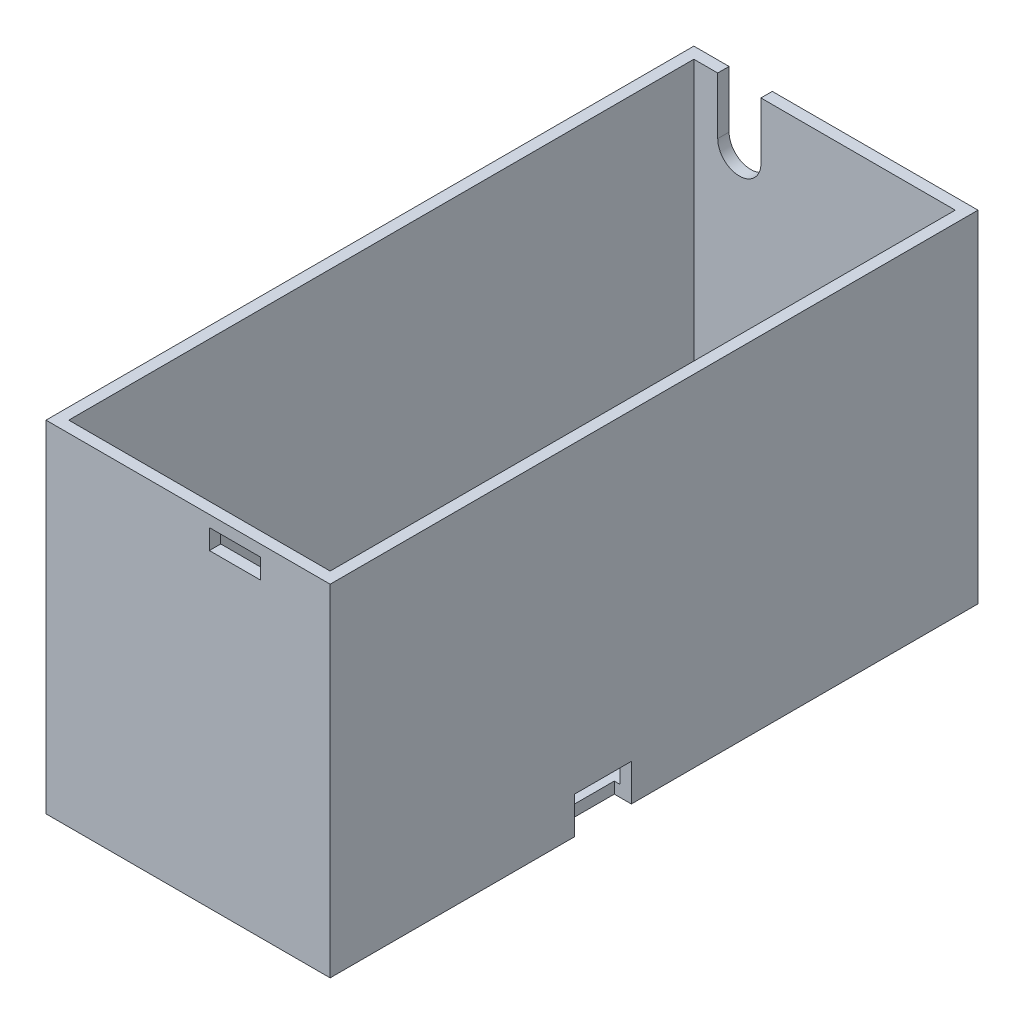
SolidWorks part; units mm, degrees
ref_plane "Ebene vorne" through (0, 0, 0) normal (0, 0, 1) x (1, 0, 0)
ref_plane "Ebene oben" through (0, 0, 0) normal (0, 1, 0) x (1, 0, 0)
ref_plane "Ebene rechts" through (0, 0, 0) normal (1, 0, 0) x (0, 0, -1)
sketch "Skizze1" plane through (0, 0, 0) normal (0, 1, 0) x (1, 0, 0)
  line L1 (-21.2423, 10.7747) -> (28.7577, 10.7747)
  line L2 (-21.2423, 10.7747) -> (-21.2423, -103.2253)
  line L3 (-21.2423, -103.2253) -> (28.7577, -103.2253)
  line L4 (28.7577, 10.7747) -> (28.7577, -103.2253)
  dimension "D1" = 50
  dimension "D2" = 114
extrude "Aufsatz-Linear austragen1" add sketch "Skizze1" along normal blind 60
sketch "Skizze2" plane through (0, 60, 0) normal (0, 1, 0) x (1, 0, 0)
  line L0 (-21.2423, 10.7747) -> (-21.2423, -103.2253) construction
  line L1 (28.7577, -103.2253) -> (28.7577, 10.7747) construction
  line L2 (-19.2423, 8.7747) -> (26.7577, 8.7747)
  line L3 (-19.2423, 8.7747) -> (-19.2423, -101.2253)
  line L4 (-19.2423, -101.2253) -> (26.7577, -101.2253)
  line L5 (26.7577, 8.7747) -> (26.7577, -101.2253)
  line L6 (28.7577, 10.7747) -> (-21.2423, 10.7747) construction
  line L7 (-21.2423, -103.2253) -> (28.7577, -103.2253) construction
  dimension "D1" = 2
  dimension "D2" = 2
  dimension "D3" = 2
  dimension "D4" = 2
extrude "Schnitt-Linear austragen1" cut sketch "Skizze2" against normal blind 58
sketch "Skizze3" plane through (0, 2, 0) normal (0, 1, 0) x (1, 0, 0)
  line L0 (3.7577, 8.7747) -> (3.7577, -101.2253) construction
  line L1 (26.7577, 8.7747) -> (-19.2423, 8.7747) construction
  line L2 (-19.2423, -101.2253) -> (26.7577, -101.2253) construction
  line L4 (-19.2423, 8.7747) -> (-19.2423, -101.2253) construction
  line L5 (-19.2423, -46.2253) -> (26.7577, -46.2253) construction
  line L6 (26.7577, -101.2253) -> (26.7577, 8.7747) construction
  circle A0 centre (-11.2423, -24.2253) radius 2
  circle A1 centre (18.7577, -24.2253) radius 2
  circle A2 centre (18.7577, -96.2253) radius 2
  circle A3 centre (-11.2423, -96.2253) radius 2
  dimension "D1" = 4
  dimension "D2" = 4
  dimension "D3" = 4
  dimension "D4" = 4
  dimension "D5" = 15
  dimension "D6" = 15
  dimension "D7" = 15
  dimension "D8" = 15
  dimension "D9" = 5
  dimension "D10" = 5
  dimension "D11" = 72
  dimension "D12" = 72
extrude "Aufsatz-Linear austragen2" add sketch "Skizze3" along normal blind 15.2
sketch "Skizze4" plane through (0, 17.2, 0) normal (0, 1, 0) x (1, 0, 0)
  circle A0 centre (-11.2423, -24.2253) radius 0.5
  circle A1 centre (18.7577, -24.2253) radius 0.5
  circle A2 centre (18.7577, -96.2253) radius 0.5
  circle A3 centre (-11.2423, -96.2253) radius 0.5
  dimension "D1" = 1
  dimension "D2" = 1
  dimension "D3" = 1
  dimension "D4" = 1
extrude "Schnitt-Linear austragen2" cut sketch "Skizze4" against normal blind 5
sketch "Skizze5" plane through (0, 2, 0) normal (0, 1, 0) x (1, 0, 0)
  line L0 (26.7577, 8.7747) -> (-19.2423, 8.7747) construction
  line L1 (-3.9923, -7.7253) -> (11.5077, -7.7253)
  line L2 (-3.9923, -7.7253) -> (-3.9923, -27.9253)
  line L3 (-3.9923, -27.9253) -> (11.5077, -27.9253)
  line L4 (11.5077, -7.7253) -> (11.5077, -27.9253)
  point P4 (3.7577, 8.7747)
  point P9 (3.7577, -7.7253)
  dimension "D1" = 15.5
  dimension "D2" = 20.2
  dimension "D3" = 16.5
extrude "Schnitt-Linear austragen3" cut sketch "Skizze5" against normal up to next
sketch "Skizze6" plane through (0, 2, 0) normal (0, 1, 0) x (1, 0, 0)
  line L0 (11.5077, -27.9253) -> (11.5077, -7.7253) construction
  line L1 (-3.9923, -27.9253) -> (11.5077, -27.9253)
  line L2 (-3.9923, -27.9253) -> (-3.9923, -29.9253)
  line L3 (-3.9923, -29.9253) -> (11.5077, -29.9253)
  line L4 (11.5077, -27.9253) -> (11.5077, -29.9253)
  dimension "D1" = 2
extrude "Aufsatz-Linear austragen3" add sketch "Skizze6" along normal blind 1
sketch "Skizze7" plane through (0, 2, 0) normal (0, 1, 0) x (1, 0, 0)
  line L0 (26.7577, 8.7747) -> (-19.2423, 8.7747) construction
  line L1 (-16.2423, -33.2253) -> (23.7577, -33.2253)
  line L2 (-16.2423, -33.2253) -> (-16.2423, -36.3253)
  line L3 (-16.2423, -36.3253) -> (23.7577, -36.3253)
  line L4 (23.7577, -33.2253) -> (23.7577, -36.3253)
  line L17 (-16.2423, -37.3253) -> (-16.2423, -40.4253)
  line L18 (-16.2423, -37.3253) -> (23.7577, -37.3253)
  line L19 (23.7577, -37.3253) -> (23.7577, -40.4253)
  line L20 (-16.2423, -40.4253) -> (23.7577, -40.4253)
  line L21 (-16.2423, -41.4253) -> (-16.2423, -44.5253)
  line L22 (-16.2423, -41.4253) -> (23.7577, -41.4253)
  line L23 (23.7577, -41.4253) -> (23.7577, -44.5253)
  line L24 (-16.2423, -44.5253) -> (23.7577, -44.5253)
  line L25 (-16.2423, -45.5253) -> (-16.2423, -48.6253)
  line L26 (-16.2423, -45.5253) -> (23.7577, -45.5253)
  line L27 (23.7577, -45.5253) -> (23.7577, -48.6253)
  line L28 (-16.2423, -48.6253) -> (23.7577, -48.6253)
  line L29 (-16.2423, -49.6253) -> (-16.2423, -52.7253)
  line L30 (-16.2423, -49.6253) -> (23.7577, -49.6253)
  line L31 (23.7577, -49.6253) -> (23.7577, -52.7253)
  line L32 (-16.2423, -52.7253) -> (23.7577, -52.7253)
  line L33 (-16.2423, -53.7253) -> (-16.2423, -56.8253)
  line L34 (-16.2423, -53.7253) -> (23.7577, -53.7253)
  line L35 (23.7577, -53.7253) -> (23.7577, -56.8253)
  line L36 (-16.2423, -56.8253) -> (23.7577, -56.8253)
  circle A1 centre (-11.2423, -24.2253) radius 0.5 construction
  point P6 (3.7577, 8.7747)
  point P7 (3.7577, -33.2253)
  dimension "D1" = 9
  dimension "D2" = 3.1
  dimension "D3" = 40
  dimension "D4" = 6
extrude "Schnitt-Linear austragen4" cut sketch "Skizze7" against normal up to next
chamfer "Fase1" distance 1.5 angle 45 24 edges at (-16.2423, 1, 41.4253) (-16.2423, 1, 37.3253) (-16.2423, 1, 45.5253) (-16.2423, 1, 49.6253) (-16.2423, 1, 53.7253) (-16.2423, 1, 40.4253) (-16.2423, 1, 48.6253) (-16.2423, 1, 44.5253) (-16.2423, 1, 52.7253) (-16.2423, 1, 56.8253) (23.7577, 1, 37.3253) (23.7577, 1, 41.4253) (23.7577, 1, 45.5253) (23.7577, 1, 49.6253) (23.7577, 1, 53.7253) (23.7577, 1, 56.8253) (23.7577, 1, 52.7253) (23.7577, 1, 48.6253) (23.7577, 1, 44.5253) (23.7577, 1, 40.4253) (23.7577, 1, 36.3253) (23.7577, 1, 33.2253) (-16.2423, 1, 33.2253) (-16.2423, 1, 36.3253)
sketch "Skizze8" plane through (28.7577, 0, 0) normal (1, 0, 0) x (0, 0, -1)
  line L0 (10.7747, 60) -> (10.7747, 0) construction
  line L1 (-60.2253, 6.5) -> (-50.2253, 6.5)
  line L2 (-60.2253, 6.5) -> (-60.2253, 0)
  line L3 (-60.2253, 0) -> (-50.2253, 0)
  line L4 (-50.2253, 6.5) -> (-50.2253, 0)
  line L5 (-103.2253, 0) -> (10.7747, 0) construction
  dimension "D1" = 61
  dimension "D2" = 0
  dimension "D3" = 10
  dimension "D4" = 6.5
extrude "Schnitt-Linear austragen5" cut sketch "Skizze8" against normal blind 3
sketch "Skizze9" plane through (0, 0, -10.7747) normal (0, 0, -1) x (-1, 0, 0)
  line L0 (-28.7577, 0) -> (21.2423, 0) construction
  line L1 (21.2423, 60) -> (21.2423, 0) construction
  line L2 (7.4423, 50) -> (7.4423, 60)
  line L3 (-28.7577, 60) -> (21.2423, 60) construction
  line L4 (15.0423, 50) -> (15.0423, 60)
  circle A0 centre (11.2423, 50) radius 3.8
  line M4 (21.2423, 60) -> (-28.7577, 60)
  dimension "D1" = 7.6
  dimension "D2" = 50
  dimension "D3" = 10
extrude "Schnitt-Linear austragen6" cut sketch "Skizze9" against normal up to next contours A0 L4 L2 M4 | A0
sketch "Skizze10" plane through (0, 0, 103.2253) normal (0, 0, 1) x (1, 0, 0)
  line L0 (28.7577, 60) -> (28.7577, 0) construction
  line L1 (7.5077, 58) -> (16.5077, 58)
  line L2 (7.5077, 58) -> (7.5077, 54.5)
  line L3 (7.5077, 54.5) -> (16.5077, 54.5)
  line L4 (16.5077, 58) -> (16.5077, 54.5)
  line L5 (-21.2423, 60) -> (28.7577, 60) construction
  dimension "D1" = 12.25
  dimension "D2" = 9
  dimension "D3" = 2
  dimension "D4" = 3.5
extrude "Schnitt-Linear austragen7" cut sketch "Skizze10" against normal up to next
